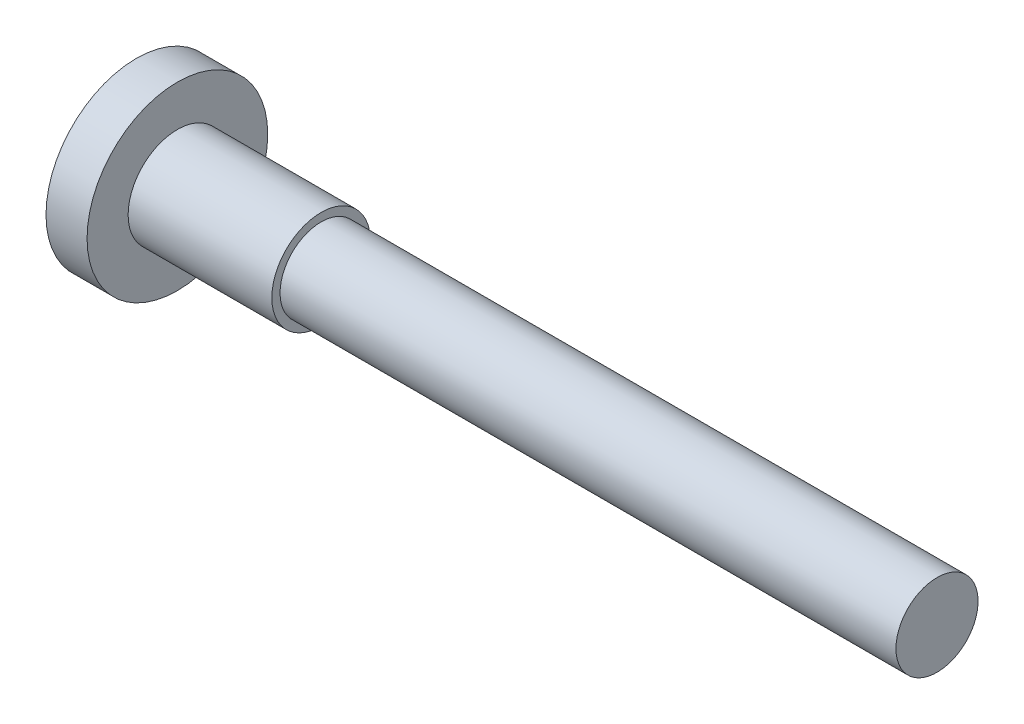
SolidWorks part; units mm, degrees
ref_plane "前视基准面" through (0, 0, 0) normal (0, 0, 1) x (1, 0, 0)
ref_plane "上视基准面" through (0, 0, 0) normal (0, 1, 0) x (1, 0, 0)
ref_plane "右视基准面" through (0, 0, 0) normal (1, 0, 0) x (0, 0, -1)
sketch "草图1" plane through (0, 0, 0) normal (0, 1, 0) x (1, 0, 0)
  line L0 (-49.6413, 0) -> (81.68, 0) construction
  line L1 (0, 86.0638) -> (0, -55.8656) construction
  line L2 (0, 0) -> (0, 11)
  line L3 (0, 11) -> (5, 11)
  line L4 (5, 11) -> (5, 6)
  line L5 (5, 6) -> (22.5, 6)
  line L6 (97.5, 5) -> (97.5, 0)
  line L7 (0, 0) -> (97.5, 0)
  line L8 (22.5, 6) -> (22.5, 5)
  line L9 (22.5, 5) -> (97.5, 5)
revolve "旋转1" add sketch "草图1" angle 360 about L0
